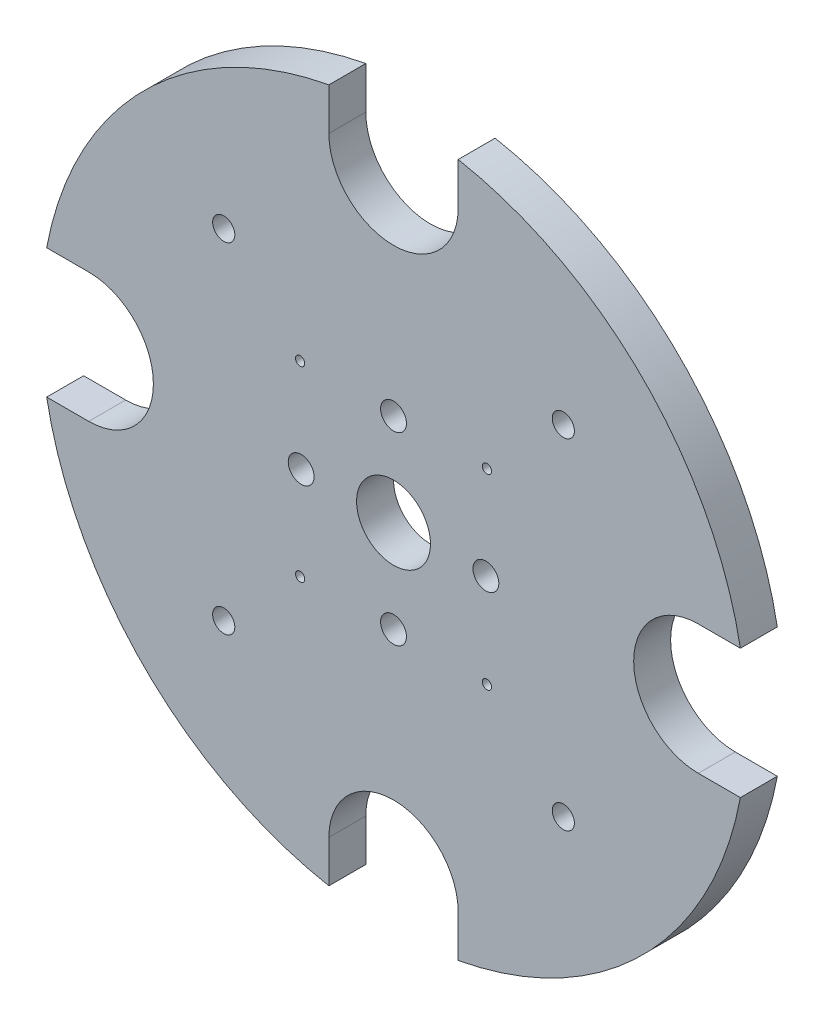
SolidWorks part; units mm, degrees
ref_plane "Plan1" through (0, 0, 0) normal (0, 0, 1) x (1, 0, 0)
ref_plane "Plan2" through (0, 0, 0) normal (0, 1, 0) x (1, 0, 0)
ref_plane "Plan3" through (0, 0, 0) normal (1, 0, 0) x (0, 0, -1)
sketch "Esquisse1" plane through (0, 0, 0) normal (0, 0, 1) x (1, 0, 0)
  line L0 (0, 0) -> (0, 114.126) construction
  line L1 (0, 0) -> (135.1767, 0) construction
  circle A0 centre (0, 0) radius 191
  dimension "D1" = 382
extrude "Base-Extrusion" add sketch "Esquisse1" along normal blind 20
sketch "Esquisse2" plane through (0, 0, 20) normal (0, 0, 1) x (1, 0, 0)
  line L0 (0, 0) -> (0, 205.2109) construction
  line L1 (0, 0) -> (227.442, 0) construction
  circle A0 centre (0, 0) radius 20
  dimension "D1" = 40
extrude "Enlèv. mat.-Extru.1" cut sketch "Esquisse2" against normal blind 20
sketch "Esquisse3" plane through (0, 0, 20) normal (0, 0, 1) x (1, 0, 0)
  circle A0 centre (50, 0) radius 7
  circle A1 centre (0, 0) radius 50 construction
  dimension "D1" = 14
  dimension "D2" = 100
extrude "Enlèv. mat.-Extru.2" cut sketch "Esquisse3" against normal blind 20
cosmetic thread "Représentation de filetage1" parameters "D2"=16
pattern_circular "Répétition circulaire1" count 4 every 90
sketch "Esquisse4" plane through (0, 0, 20) normal (0, 0, 1) x (1, 0, 0)
  line L1 (0, 0) -> (237.7026, 0) construction
  line L2 (0, 0) -> (91.9239, 91.9239) construction
  circle A0 centre (91.9239, 91.9239) radius 6
  circle A1 centre (50.5581, 50.5581) radius 2.5
  circle A2 centre (0, 0) radius 71.5 construction
  circle A3 centre (0, 0) radius 130 construction
  dimension "D2" = 12
  dimension "D3" = 5
  dimension "D5" = 143
  dimension "D4" = 260
  dimension "D1" = 45
extrude "Enlèv. mat.-Extru.3" cut sketch "Esquisse4" against normal blind 20
cosmetic thread "Représentation de filetage2" parameters "D2"=6
pattern_circular "Répétition circulaire2" count 4 every 90
sketch "Esquisse5" plane through (0, 0, 20) normal (0, 0, 1) x (1, 0, 0)
  line L1 (0, 0) -> (0, 207.263) construction
  line L2 (-35, 187.7658) -> (-35, 165)
  line L4 (35, 165) -> (35, 187.7658)
  circle A0 centre (0, 0) radius 191 construction
  arc A1 (-35, 165) -> (35, 165) centre (0, 165) ccw
  arc A2 (35, 187.7658) -> (-35, 187.7658) centre (0, 0) ccw
  circle A3 centre (0, 0) radius 20 construction
  dimension "D1" = 165
  dimension "D2" = 70
extrude "Enlèv. mat.-Extru.4" cut sketch "Esquisse5" against normal through all
pattern_circular "Répétition circulaire3" count 4 every 90
